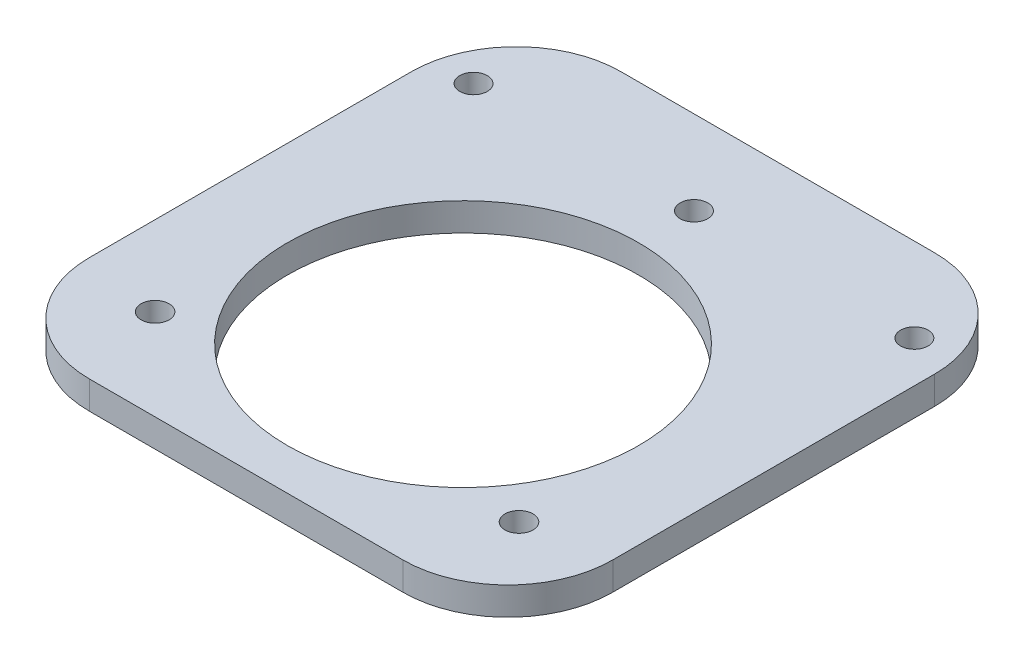
SolidWorks part; units mm, degrees
material "6061 Alloy"
ref_plane "Front Plane" through (0, 0, 0) normal (0, 0, 1) x (1, 0, 0)
ref_plane "Top Plane" through (0, 0, 0) normal (0, 1, 0) x (1, 0, 0)
ref_plane "Right Plane" through (0, 0, 0) normal (1, 0, 0) x (0, 0, -1)
sketch "Sketch2" plane through (0, 0, 0) normal (0, 1, 0) x (1, 0, 0)
  line L0 (0, 0) -> (0, 35.56) construction
  line L1 (-47.5, -60.96) -> (-47.5, 35.56)
  line L2 (47.5, -60.96) -> (47.5, 35.56)
  line L3 (-47.5, 35.56) -> (47.5, 35.56)
  line L4 (-47.5, -60.96) -> (47.5, -60.96)
  point P3 (47.5, -12.7)
  point P5 (0, 35.56)
  point P12 (0, -60.96)
  dimension "D1" = 96.52
  dimension "D2" = 95
  dimension "D3" = 12.7
extrude "Boss-Extrude3" add sketch "Sketch2" along normal blind 5.08
sketch "Sketch3" plane through (0, 5.08, 0) normal (0, 1, 0) x (1, 0, 0)
  line L0 (47.5, 35.56) -> (-47.5, 35.56) construction
  circle A1 centre (0, -21.59) radius 31.88
  dimension "D2" = 63.76
  dimension "D3" = 57.15
extrude "Cut-Extrude1" cut sketch "Sketch3" against normal through all
sketch "Sketch4" plane through (0, 5.08, 0) normal (0, 1, 0) x (1, 0, 0)
  line L0 (47.5, 35.56) -> (-47.5, 35.56) construction
  line L1 (0, 35.56) -> (0, 55.3884) construction
  point P0 (-40, 20.32)
  point P7 (40, 20.32)
  point P8 (0, 20.32)
  point P10 (0, 20.32)
  dimension "D1" = 15.24
  dimension "D2" = 80
hole_wizard "M6x1.0 Tapped Hole1" positions "Sketch4" profile "Sketch6" tap size "M6x1.0" standard "ANSI Metric"
sketch "Sketch6" plane through (-40, 5.08, -20.32) normal (1, 0, 0) x (0, 0, 1)
  line L0 (0, 0) -> (0, 6.5822)
  line L1 (0, 6.5822) -> (2.5, 5.08)
  line L2 (2.5, 5.08) -> (2.5, 0)
  line L5 (2.5, 0) -> (0, 0)
  line L10 (0, 6.5822) -> (-2.5, 5.08) construction
  line L11 (0, -6.35) -> (0, 107.95) construction
  dimension "Tap Drill Dia." = 5
  dimension "Tap Drill Depth" = 5.08
  dimension "Drill Angle" = 118
sketch "Sketch7" plane through (0, 5.08, 0) normal (0, 1, 0) x (1, 0, 0)
  line L0 (0, 0) -> (0, -60.96) construction
  line L1 (-47.5, -60.96) -> (47.5, -60.96) construction
  circle A0 centre (-33.02, -44.45) radius 2.54
  circle A1 centre (33.02, -44.45) radius 2.54
  dimension "D3" = 5.08
  dimension "D1" = 44.45
  dimension "D2" = 33.02
extrude "Cut-Extrude2" cut sketch "Sketch7" against normal blind 7.62
fillet "Fillet1" radius 19.05 4 edges at (47.5, 2.54, -35.56) (47.5, 2.54, 60.96) (-47.5, 2.54, 60.96) (-47.5, 2.54, -35.56)
